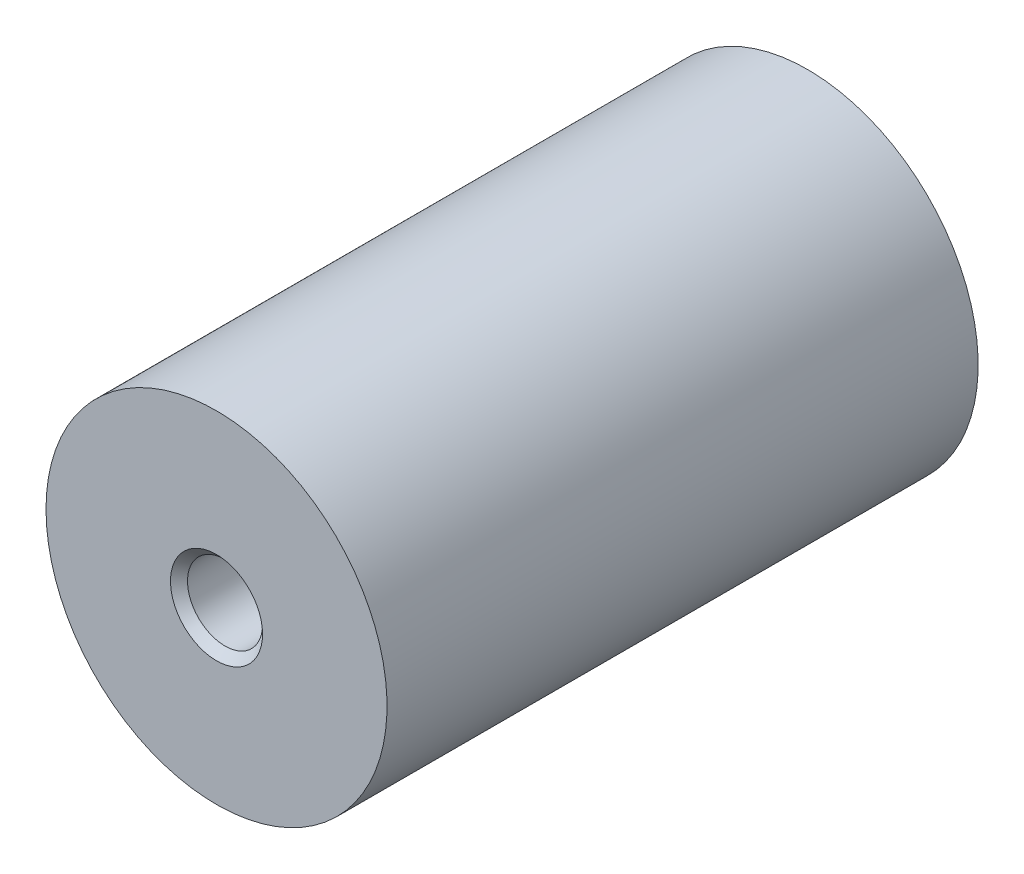
SolidWorks part; units mm, degrees
ref_plane "Front Plane" through (0, 0, 0) normal (0, 0, 1) x (1, 0, 0)
ref_plane "Top Plane" through (0, 0, 0) normal (0, 1, 0) x (1, 0, 0)
ref_plane "Right Plane" through (0, 0, 0) normal (1, 0, 0) x (0, 0, -1)
sketch "Sketch1" plane through (0, 0, 0) normal (0, 0, 1) x (1, 0, 0)
  circle A0 centre (0, 0) radius 7.5
  dimension "D1" = 15
extrude "Boss-Extrude1" add sketch "Sketch1" along normal mid plane 26
hole_wizard "M4x0.7 Tapped Hole1" positions "Sketch2" profile "Sketch3" tap size "M4x0.7" standard "ANSI Metric" end condition through all
sketch "Sketch2" plane through (0, 0, 13) normal (0, 0, 1) x (1, 0, 0)
  point P0 (0, 0)
sketch "Sketch3" plane through (0, 0, 13) normal (1, 0, 0) x (0, -1, 0)
  line L0 (0, 0) -> (0, 26)
  line L1 (0, 26) -> (1.65, 26)
  line L2 (1.65, 26) -> (1.65, 0.375)
  line L3 (1.65, 0.375) -> (2.025, 0)
  line L5 (2.025, 0) -> (0, 0)
  line L6 (-1.65, 0.375) -> (-2.025, 0) construction
  line L11 (0, -6.35) -> (0, 107.95) construction
  dimension "Thru Tap Drill Dia." = 3.3
  dimension "Thru Tap Drill Depth" = 26
  dimension "Near C'Sink Dia." = 4.05
  dimension "Near C'Sink Angle" = 90
